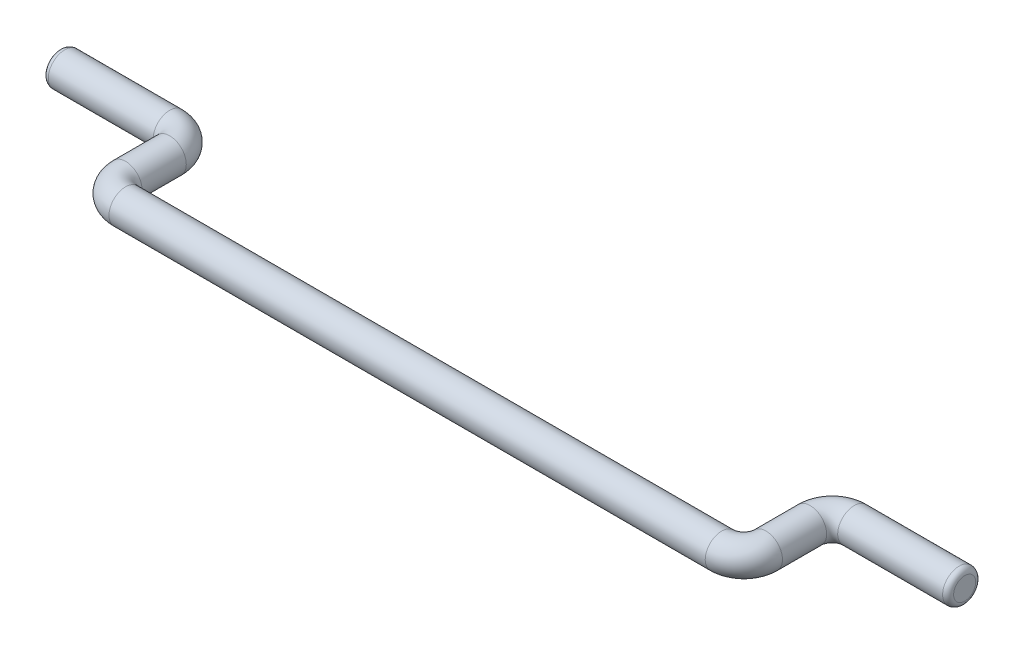
SolidWorks part; units mm, degrees
ref_plane "Front Plane" through (0, 0, 0) normal (0, 0, 1) x (1, 0, 0)
ref_plane "Top Plane" through (0, 0, 0) normal (0, 1, 0) x (1, 0, 0)
ref_plane "Right Plane" through (0, 0, 0) normal (1, 0, 0) x (0, 0, -1)
sketch "Sketch1" plane through (0, 0, 0) normal (0, 1, 0) x (1, 0, 0)
  line L0 (-6, 0) -> (-1, 0)
  line L1 (0, -1) -> (0, -3)
  line L2 (1, -4) -> (28, -4)
  line L3 (29, -3) -> (29, -1)
  line L4 (30, 0) -> (35, 0)
  arc A0 (29, -1) -> (30, 0) centre (30, -1) cw
  arc A1 (28, -4) -> (29, -3) centre (28, -3) ccw
  arc A2 (0, -3) -> (1, -4) centre (1, -3) ccw
  arc A3 (-1, 0) -> (0, -1) centre (-1, -1) cw
  point P7 (29, -2)
  point P11 (29, 0)
  point P16 (0, -4)
  point P19 (0, 0)
  dimension "D5" = 1
  dimension "D1" = 29
  dimension "D2" = 4
  dimension "D3" = 6
  dimension "D4" = 6
ref_plane "Plane1" through (-6, 0, 0) normal (1, 0, 0) x (0, 0, -1)
sketch "Sketch3" plane through (-6, 0, 0) normal (1, 0, 0) x (0, 0, -1)
  circle A0 centre (0, 0) radius 0.75
  dimension "D1" = 1.5
sweep "Sweep1" add profiles "Sketch3" path "Sketch1"
fillet "Fillet1" radius 0.25 2 edges at (35, 0, -0.75) (-6, 0, -0.75)
